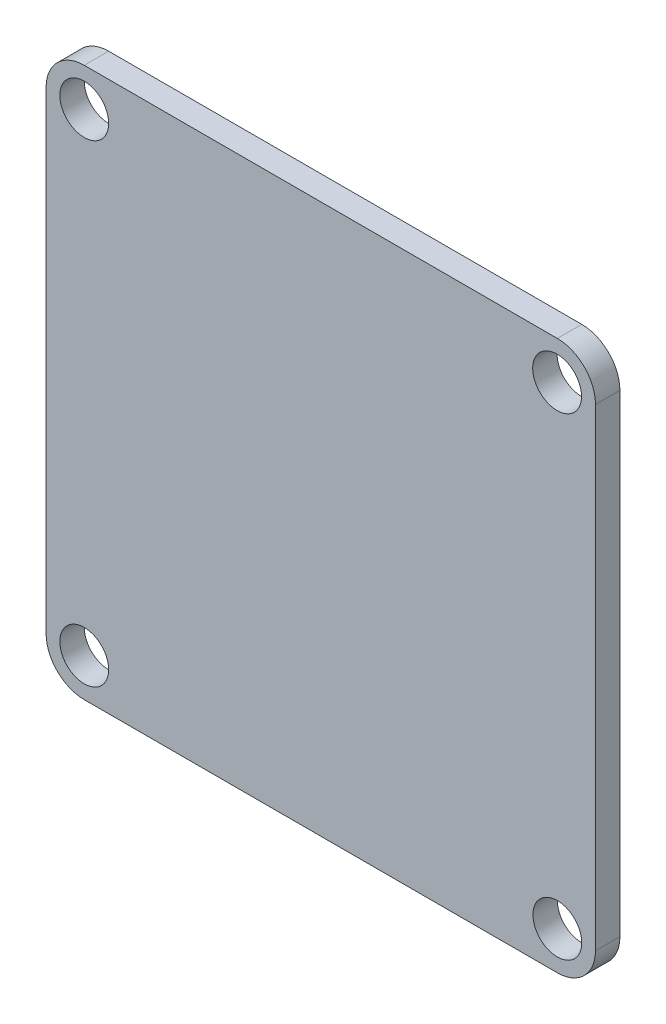
SolidWorks part; units mm, degrees
ref_plane "Front Plane" through (0, 0, 0) normal (0, 0, 1) x (1, 0, 0)
ref_plane "Top Plane" through (0, 0, 0) normal (0, 1, 0) x (1, 0, 0)
ref_plane "Right Plane" through (0, 0, 0) normal (1, 0, 0) x (0, 0, -1)
sketch "Sketch2" plane through (0, 0, 0) normal (0, 0, 1) x (1, 0, 0)
  line L1 (18, 18) -> (-18, 18)
  line L2 (18, 18) -> (18, -18)
  line L3 (18, -18) -> (-18, -18)
  line L4 (-18, 18) -> (-18, -18)
  line L5 (18, 18) -> (-18, -18) construction
  line L6 (18, -18) -> (-18, 18) construction
  point P0 (0, 0)
  dimension "D1" = 36
  dimension "D2" = 36
extrude "Boss-Extrude1" add sketch "Sketch2" along normal blind 1.6
fillet "Fillet1" radius 2.5 4 edges at (18, 18, 0.8) (18, -18, 0.8) (-18, -18, 0.8) (-18, 18, 0.8)
sketch "Sketch3" plane through (0, 0, 1.6) normal (0, 0, 1) x (1, 0, 0)
  line L0 (-18, 0) -> (18, 0) construction
  line L1 (0, -18) -> (0, 18) construction
  line L2 (-15.5, -18) -> (15.5, -18) construction
  line L3 (15.5, 18) -> (-15.5, 18) construction
  line L4 (18, -15.5) -> (18, 15.5) construction
  line L5 (-18, 15.5) -> (-18, -15.5) construction
  circle A0 centre (-15.5, -15.5) radius 1.6
  circle A1 centre (-15.5, 15.5) radius 1.6
  circle A2 centre (15.4853, 15.5) radius 1.6
  circle A3 centre (15.5, -15.5) radius 1.6
  dimension "D1" = 3.2
  dimension "D2" = 3.2
  dimension "D3" = 3.2
  dimension "D4" = 3.2
  dimension "D5" = 2.5
  dimension "D6" = 2.5
  dimension "D7" = 2.5
  dimension "D8" = 2.5
  dimension "D9" = 2.5147
  dimension "D10" = 2.5
  dimension "D11" = 2.5
  dimension "D12" = 2.5
extrude "Cut-Extrude1" cut sketch "Sketch3" against normal up to next
